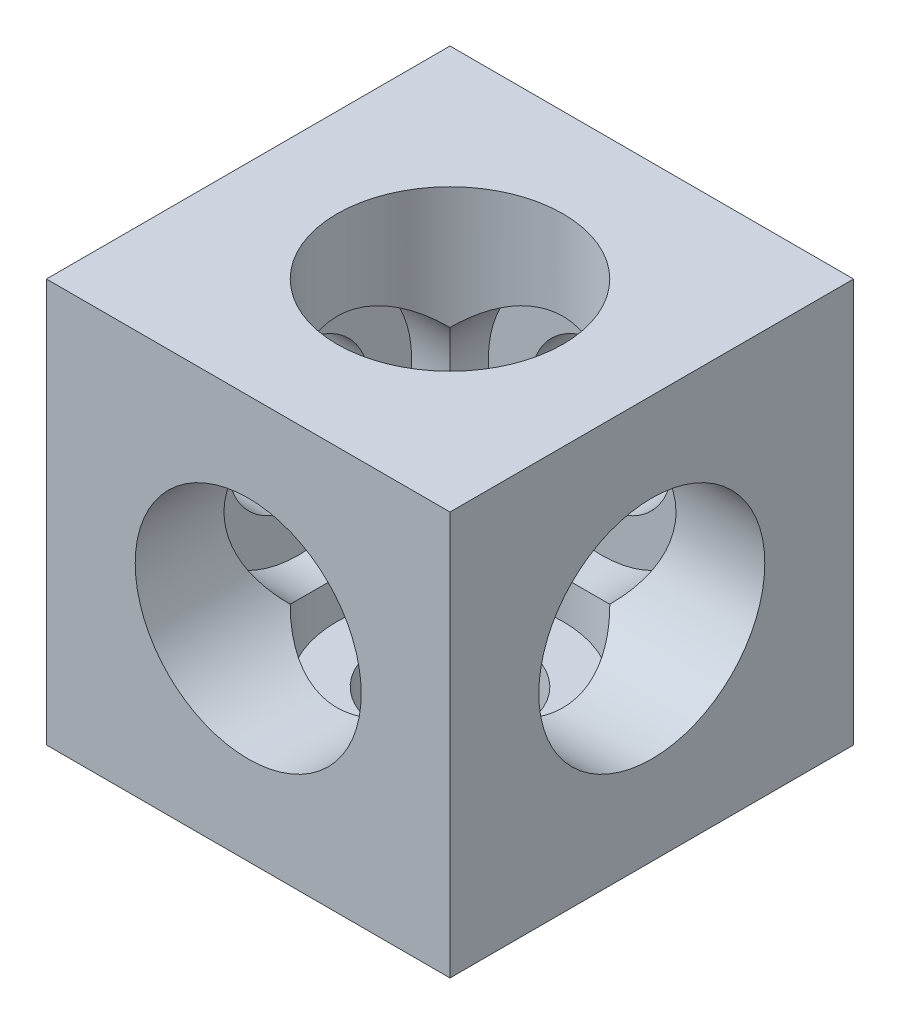
SolidWorks part; units mm, degrees
ref_plane "Front Plane" through (0, 0, 0) normal (0, 0, 1) x (1, 0, 0)
ref_plane "Top Plane" through (0, 0, 0) normal (0, 1, 0) x (1, 0, 0)
ref_plane "Right Plane" through (0, 0, 0) normal (1, 0, 0) x (0, 0, -1)
ref_plane "Plane1" through (0, 10, 0) normal (0, 1, 0) x (1, 0, 0)
sketch "Sketch1" plane through (0, 10, 0) normal (0, 1, 0) x (1, 0, 0)
  line L0 (-10, 10) -> (-10, -10)
  line L1 (-10, -10) -> (10, -10)
  line L2 (10, -10) -> (10, 10)
  line L3 (10, 10) -> (-10, 10)
extrude "Boss-Extrude1" add sketch "Sketch1" against normal blind 20
ref_plane "Plane2" through (0, 0, 0) normal (0, 0, -1) x (-1, 0, 0)
sketch "Sketch2" plane through (0, 0, 0) normal (0, 0, -1) x (-1, 0, 0)
  line L0 (-3.5, -10) -> (0, -10)
  line L1 (0, -10) -> (0, 10)
  line L2 (0, 10) -> (-5.6, 10)
  line L3 (-5.6, 10) -> (-5.6, -7.5)
  line L4 (-5.6, -7.5) -> (-3.5, -7.5)
  line L5 (-3.5, -7.5) -> (-3.5, -10)
  line L6 (0, -10) -> (0, 10) construction
revolve "Cut-Revolve1" cut sketch "Sketch2" angle 360 about L6
hole_wizard "Hole1" positions "Sketch4" profile "Sketch3" legacy
sketch "Sketch4" plane through (0, 0, 10) normal (0, 0, 1) x (1, 0, 0)
  point P0 (0, 0)
sketch "Sketch3" plane through (0, 0, 10) normal (1, 0, 0) x (0, -1, 0)
  line L0 (0, 0) -> (0, 20)
  line L1 (0, 20) -> (3.5, 20)
  line L2 (3.5, 20) -> (3.5, 17.5)
  line L3 (3.5, 17.5) -> (5.6, 17.5)
  line L4 (5.6, 17.5) -> (5.6, 0)
  line L5 (5.6, 0) -> (0, 0)
  line L6 (0, 110) -> (0, -10) construction
  dimension "Diameter" = 7
  dimension "Depth" = 20
  dimension "C-Bore Diameter" = 11.2
  dimension "C-Bore Depth" = 17.5
hole_wizard "Hole2" positions "Sketch6" profile "Sketch5" legacy
sketch "Sketch6" plane through (10, 0, 0) normal (1, 0, 0) x (0, 0, -1)
  point P0 (0, 0)
sketch "Sketch5" plane through (10, 0, 0) normal (0, 1, 0) x (0, 0, -1)
  line L0 (0, 0) -> (0, 20)
  line L1 (0, 20) -> (3.5, 20)
  line L2 (3.5, 20) -> (3.5, 17.5)
  line L3 (3.5, 17.5) -> (5.6, 17.5)
  line L4 (5.6, 17.5) -> (5.6, 0)
  line L5 (5.6, 0) -> (0, 0)
  line L6 (0, 110) -> (0, -10) construction
  dimension "Diameter" = 7
  dimension "Depth" = 20
  dimension "C-Bore Diameter" = 11.2
  dimension "C-Bore Depth" = 17.5
